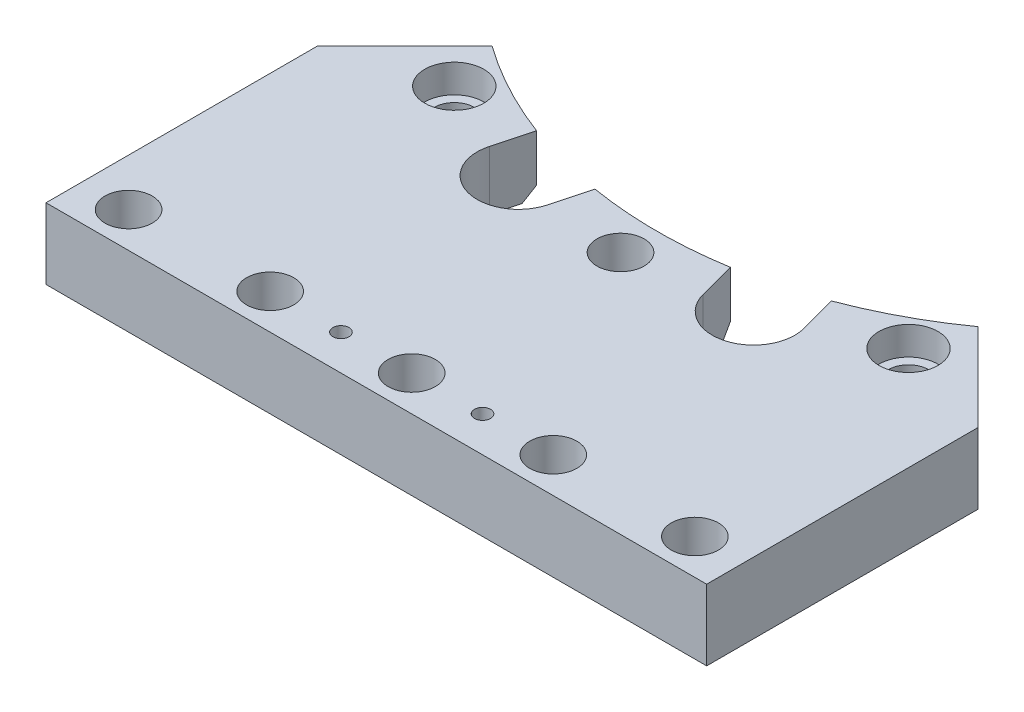
SolidWorks part; units mm, degrees
ref_plane "前视基准面" through (0, 0, 0) normal (0, 0, 1) x (1, 0, 0)
ref_plane "上视基准面" through (0, 0, 0) normal (0, 1, 0) x (1, 0, 0)
ref_plane "右视基准面" through (0, 0, 0) normal (1, 0, 0) x (0, 0, -1)
sketch "草图1" plane through (0, 0, 0) normal (0, 1, 0) x (1, 0, 0)
  line L0 (-140, 0) -> (140, 0)
  line L1 (140, 0) -> (140, 115)
  line L2 (140, 115) -> (102.9676, 152.0324)
  line L3 (-102.9676, 152.0324) -> (-140, 115)
  line L4 (-140, 115) -> (-140, 0)
  line L5 (0, 0) -> (0, 152.0324) construction
  line L6 (0, 296) -> (-123.8138, -166.0793) construction
  line L7 (32.919, 105.5299) -> (28.6828, 121.3395)
  line L10 (-66.7264, 114.5886) -> (-62.4902, 130.3981)
  line L13 (-32.919, 105.5299) -> (-28.6828, 121.3395)
  line L14 (66.7264, 114.5886) -> (62.4902, 130.3981)
  line L15 (0, 296) -> (-212.4737, -72.0152) construction
  arc A0 (102.9676, 152.0324) -> (62.4902, 130.3981) centre (0, 296) cw
  circle A2 centre (0, 296) radius 192.5 construction
  arc A8 (-66.7264, 114.5886) -> (-32.919, 105.5299) centre (-49.8227, 110.0593) ccw
  arc A9 (-62.4902, 130.3981) -> (-102.9676, 152.0324) centre (0, 296) cw
  arc A10 (66.7264, 114.5886) -> (32.919, 105.5299) centre (49.8227, 110.0593) cw
  arc A11 (28.6828, 121.3395) -> (-28.6828, 121.3395) centre (0, 296) cw
  circle A12 centre (0, 103.5) radius 10
  circle A13 centre (-96.25, 129.2901) radius 8.5
  circle A14 centre (96.25, 129.2901) radius 8.5
  point P6 (0, 0)
  dimension "D4" = 296
  dimension "D5" = 177
  dimension "D6" = 192.5
  dimension "D8" = 35
  dimension "D9" = 20
  dimension "D11" = 17
  dimension "D1" = 280
  dimension "D2" = 115
  dimension "D3" = 135
  dimension "D7" = 15
  dimension "D10" = 30
extrude "凸台-拉伸1" add sketch "草图1" along normal blind 30
sketch "草图3" plane through (0, 30, 0) normal (0, 1, 0) x (1, 0, 0)
  circle A0 centre (-96.25, 129.2901) radius 12.5
  circle A1 centre (96.25, 129.2901) radius 12.5
  dimension "D1" = 25
  dimension "D2" = 25
extrude "切除-拉伸1" cut sketch "草图3" against normal blind 12
sketch "草图4" plane through (0, 30, 0) normal (0, 1, 0) x (1, 0, 0)
  line L0 (-140, 0) -> (140, 0) construction
  line L1 (-140, 115) -> (-140, 0) construction
  circle A0 centre (-120, 15) radius 6.5
  dimension "D1" = 13
  dimension "D2" = 15
  dimension "D3" = 20
extrude "切除-拉伸2" cut sketch "草图4" against normal up to next
sketch "草图5" plane through (0, 30, 0) normal (0, 1, 0) x (1, 0, 0)
  circle A0 centre (-120, 15) radius 10
  dimension "D1" = 20
extrude "切除-拉伸3" cut sketch "草图5" against normal blind 16
pattern_linear "阵列(线性)1" count 5 spacing 60 along (1, 0, 0) of "切除-拉伸2", "切除-拉伸3"
sketch "草图6" plane through (0, 30, 0) normal (0, 1, 0) x (1, 0, 0)
  line L0 (-60, 15) -> (60, 15) construction
  line L1 (0, 15) -> (0, 55.6309) construction
  circle A0 centre (-30, 15) radius 3.4
  circle A1 centre (30, 15) radius 3.4
  dimension "D1" = 6.8
  dimension "D2" = 30
extrude "切除-拉伸4" cut sketch "草图6" against normal up to next
sketch "草图7" plane through (0, 0, 0) normal (0, -1, 0) x (1, 0, 0)
  line L0 (-102.9676, -152.0324) -> (-140, -115) construction
  line L1 (140, -115) -> (102.9676, -152.0324) construction
  line L2 (131.5666, -123.4334) -> (131.5666, -152.0324)
  line L3 (131.5666, -152.0324) -> (-131.5666, -152.0324)
  line L4 (-131.5666, -152.0324) -> (-131.5666, -123.4334)
  arc A2 (35.1648, -81.8682) -> (-35.1648, -81.8682) centre (0, -296) ccw
  arc A3 (131.5666, -123.4334) -> (-131.5666, -123.4334) centre (0, -296) ccw
  dimension "D1" = 40
extrude "切除-拉伸5" cut sketch "草图7" against normal blind 5
chamfer "倒角1" distance 5 3 edges at (-83.4331, 5, -139.8977) (0, 5, -119) (83.4331, 5, -139.8977)
